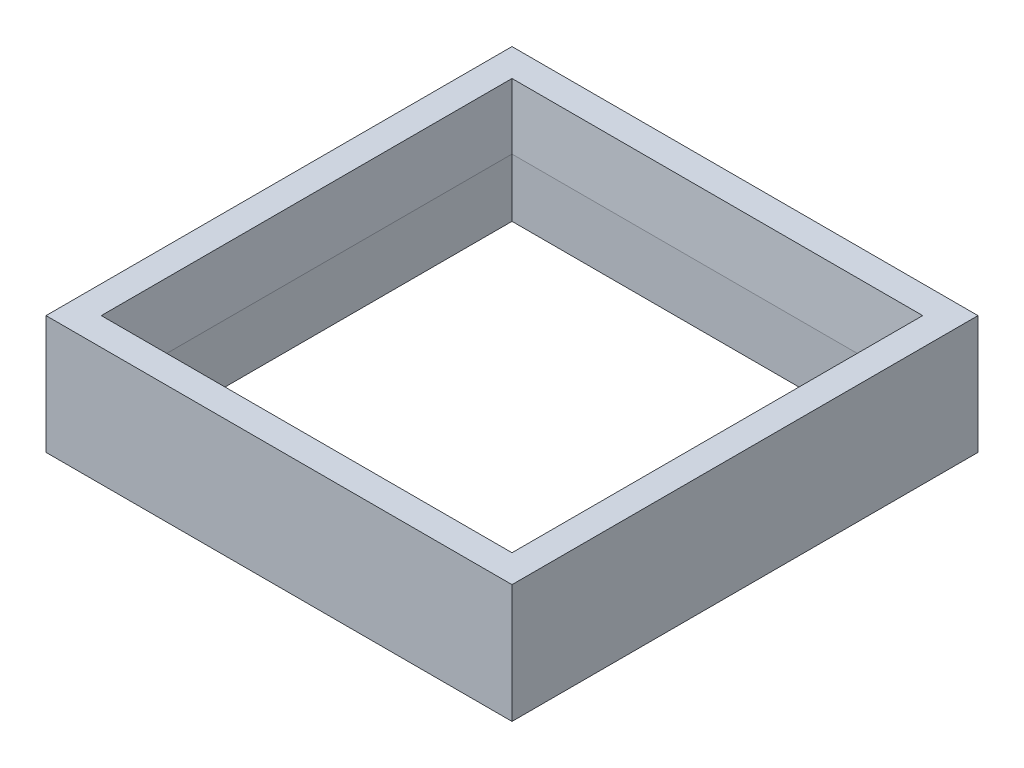
SolidWorks part; units mm, degrees
ref_plane "Front Plane" through (0, 0, 0) normal (0, 0, 1) x (1, 0, 0)
ref_plane "Top Plane" through (0, 0, 0) normal (0, 1, 0) x (1, 0, 0)
ref_plane "Right Plane" through (0, 0, 0) normal (1, 0, 0) x (0, 0, -1)
sketch "Sketch1" plane through (0, 0, 0) normal (0, 1, 0) x (1, 0, 0)
  line L1 (-19.304, -19.304) -> (19.304, -19.304)
  line L2 (-19.304, -19.304) -> (-19.304, 19.304)
  line L3 (-19.304, 19.304) -> (19.304, 19.304)
  line L4 (19.304, -19.304) -> (19.304, 19.304)
  line L5 (-19.304, -19.304) -> (19.304, 19.304) construction
  line L6 (-19.304, 19.304) -> (19.304, -19.304) construction
  line L7 (22.479, -22.479) -> (-22.479, -22.479)
  line L8 (22.479, -22.479) -> (22.479, 22.479)
  line L9 (22.479, 22.479) -> (-22.479, 22.479)
  line L10 (-22.479, -22.479) -> (-22.479, 22.479)
  line L11 (22.479, -22.479) -> (-22.479, 22.479) construction
  line L12 (22.479, 22.479) -> (-22.479, -22.479) construction
  point P0 (0, 0)
  point P6 (0, 0)
  dimension "D1" = 38.608
  dimension "D2" = 3.175
extrude "Boss-Extrude1" add sketch "Sketch1" along normal blind 11.43
chamfer "Chamfer1" distance 0.508 angle 85 4 edges at (0, 11.43, 19.304) (19.304, 11.43, 0) (0, 11.43, -19.304) (-19.304, 11.43, 0)
